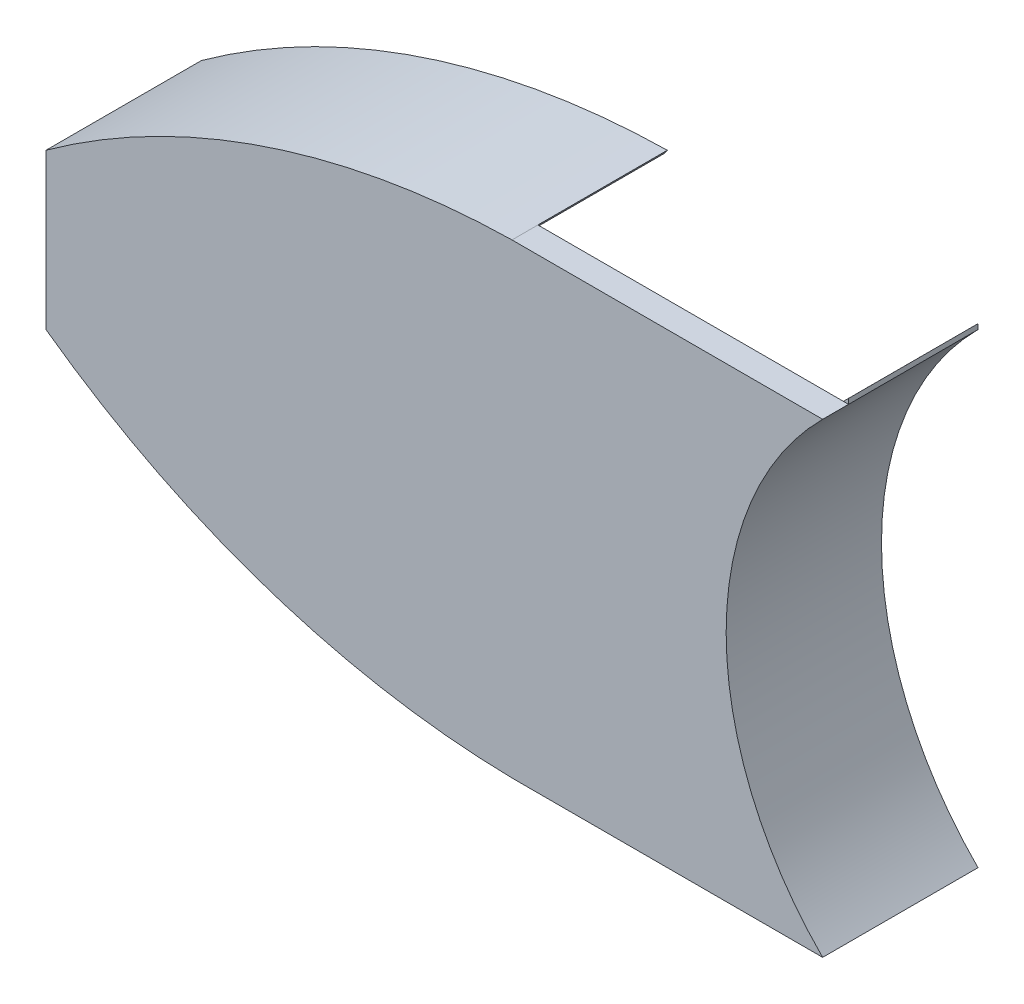
SolidWorks part; units mm, degrees
ref_plane "Front Plane" through (0, 0, 0) normal (0, 0, 1) x (1, 0, 0)
ref_plane "Top Plane" through (0, 0, 0) normal (0, 1, 0) x (1, 0, 0)
ref_plane "Right Plane" through (0, 0, 0) normal (1, 0, 0) x (0, 0, -1)
sketch "Sketch1" plane through (0, 0, 0) normal (0, 0, 1) x (1, 0, 0)
  line L0 (-300, 90) -> (6.8309, 90) construction
  line L1 (0, 0) -> (-120, 0)
  line L3 (0, 180) -> (-120, 180)
  line L4 (-300, 60) -> (-300, 120)
  arc A2 (-300, 120) -> (-120, 180) centre (-114.4729, -136.5812) cw
  arc A3 (-300, 60) -> (-120, 0) centre (-114.4729, 316.5812) ccw
  arc A4 (0, 180) -> (0, 0) centre (90, 90) ccw
  point P7 (-300, 0)
  point P10 (-300, 180)
  dimension "D3" = 316.6294
  dimension "D4" = 127.2792
  dimension "D1" = 300
  dimension "D2" = 180
  dimension "D5" = 114.4729
  dimension "D6" = 120
extrude "Boss-Extrude1" add sketch "Sketch1" along normal blind 10
sketch3d "3DSketch2"
  line L1 (0, 0, 0) -> (0, 0, -50)
  line L2 (0, 0, 0) -> (-2, 0, 0)
  line L3 (-2, 0, 0) -> (-2, 0, -50)
  line L4 (0, 0, -50) -> (-2, 0, -50)
  dimension "D1" = 50
  dimension "D2" = 2
sweep "Sweep2" add profiles "3DSketch2" path edge at (-37.2792, 90, 0)
sketch "Sketch3" plane through (-300, 0, 0) normal (-1, 0, 0) x (0, 0, 1)
  line L1 (0, 60) -> (-50, 60)
  line L2 (0, 60) -> (0, 62)
  line L3 (0, 62) -> (-50, 62)
  line L4 (-50, 60) -> (-50, 62)
  dimension "D1" = 50
  dimension "D2" = 2
sweep "Sweep3" add profiles "Sketch3" path edge at (-214.6, 16.2001, 0)
sketch "Sketch4" plane through (-300, 0, 0) normal (-1, 0, 0) x (0, 0, 1)
  line L1 (0, 120) -> (-50, 120)
  line L2 (0, 120) -> (0, 118)
  line L3 (0, 118) -> (-50, 118)
  line L4 (-50, 120) -> (-50, 118)
  dimension "D1" = 50
  dimension "D2" = 2
sweep "Sweep4" add profiles "Sketch4" path edge at (-214.6, 163.7999, 0)
sketch "Sketch5" plane through (0, 0, 0) normal (0, 0, 1) x (1, 0, 0)
  line L1 (0, 180) -> (-120, 180)
  line L2 (0, 180) -> (0, 178)
  line L3 (0, 178) -> (-120, 178)
  line L4 (-120, 180) -> (-120, 178)
  point P5 (-120, 179)
  dimension "D1" = 120
  dimension "D2" = 2
sketch "Sketch6" plane through (0, 0, 0) normal (0, 0, -1) x (-1, 0, 0)
  line L4 (120, 180) -> (120, 178)
  line L6 (120, 180) -> (120, 178)
  arc A0 (2, 0) -> (2, 180) centre (-90, 90) ccw construction
  point P13 (3.9149, 178)
